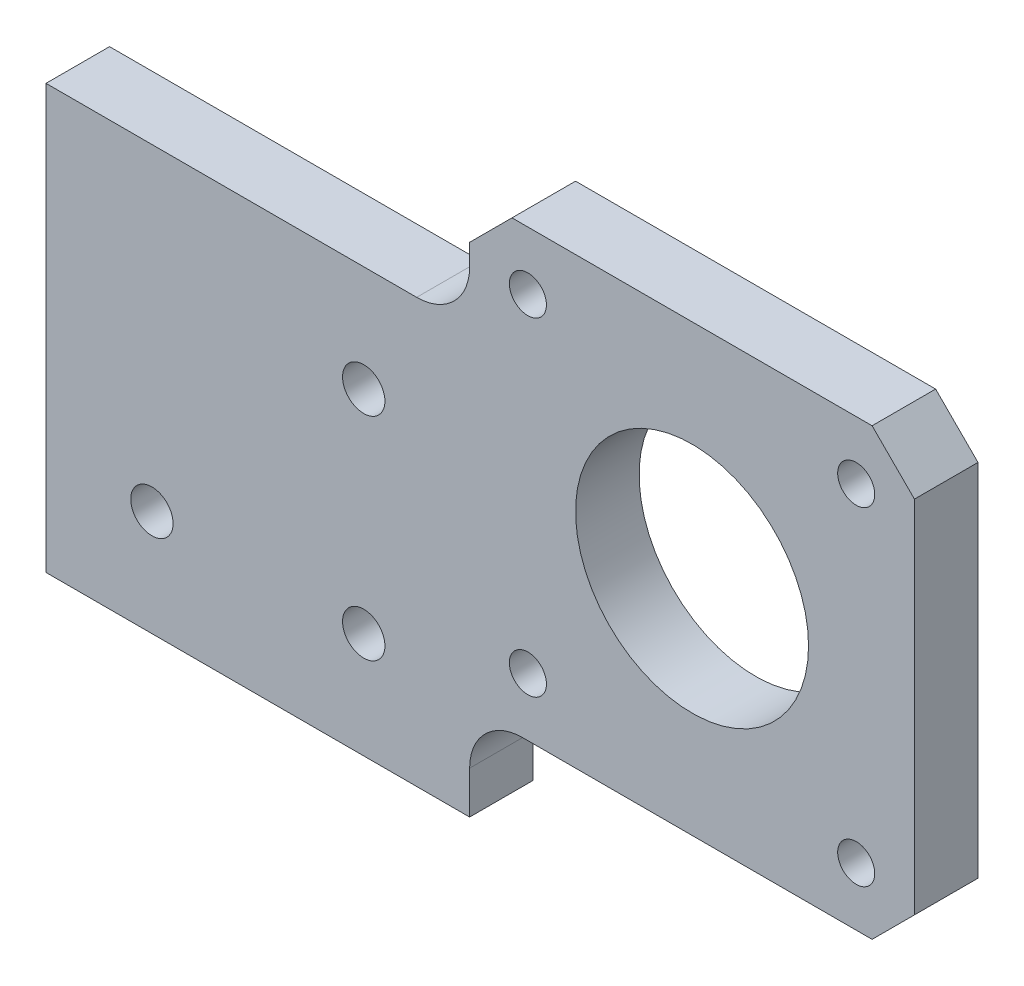
SolidWorks part; units mm, degrees
ref_plane "Plano frontal" through (0, 0, 0) normal (0, 0, 1) x (1, 0, 0)
ref_plane "Plano superior" through (0, 0, 0) normal (0, 1, 0) x (1, 0, 0)
ref_plane "Plano direito" through (0, 0, 0) normal (1, 0, 0) x (0, 0, -1)
sketch "Esboço1" plane through (0, 0, 0) normal (0, 0, 1) x (1, 0, 0)
  line L0 (30, 0) -> (30, 40) construction
  line L1 (0, 0) -> (40, 0)
  line L2 (0, 0) -> (0, 40)
  line L3 (0, 40) -> (40, 40)
  line L4 (40, 0) -> (40, 40)
  line L5 (40, 9) -> (82, 9)
  line L6 (40, 9) -> (40, 51)
  line L7 (40, 51) -> (82, 51)
  line L8 (82, 9) -> (82, 51)
  line L9 (45.5, 45.5) -> (76.5, 45.5) construction
  line L10 (45.5, 45.5) -> (45.5, 14.5) construction
  line L11 (45.5, 14.5) -> (76.5, 14.5) construction
  line L12 (76.5, 45.5) -> (76.5, 14.5) construction
  line L13 (45.5, 45.5) -> (76.5, 14.5) construction
  line L14 (45.5, 14.5) -> (76.5, 45.5) construction
  line L15 (0, 10) -> (40, 10) construction
  line L16 (10, 0) -> (10, 40) construction
  line L17 (0, 30) -> (40, 30) construction
  line L18 (61, 51) -> (61, 9) construction
  line L19 (82, 30) -> (40, 30) construction
  circle A0 centre (45.5, 45.5) radius 1.75
  circle A1 centre (76.5, 45.5) radius 1.75
  circle A2 centre (76.5, 14.5) radius 1.75
  circle A3 centre (45.5, 14.5) radius 1.75
  circle A4 centre (61, 30) radius 11
  circle A5 centre (30, 10) radius 2
  circle A6 centre (10, 10) radius 2
  circle A7 centre (30, 30) radius 2
  point P9 (82, 30)
  point P10 (61, 30)
  dimension "D5" = 3.5
  dimension "D6" = 22
  dimension "D11" = 4
  dimension "D1" = 40
  dimension "D2" = 40
  dimension "D3" = 42
  dimension "D4" = 30
  dimension "D12" = 31
  dimension "D7" = 10
  dimension "D8" = 10
  dimension "D9" = 20
  dimension "D10" = 10
extrude "Ressalto-extrusão1" add sketch "Esboço1" along normal blind 6 contours L1 L4 L3 L2 A7 A6 A5 | L5 L8 L7 L6 L4 A4 A3 A2 A1 A0
chamfer "Chanfro1" distance 4 angle 45 3 edges at (40, 51, 3) (82, 9, 3) (82, 51, 3)
fillet "Filete1" radius 5 2 edges at (40, 9, 3) (40, 40, 3)
